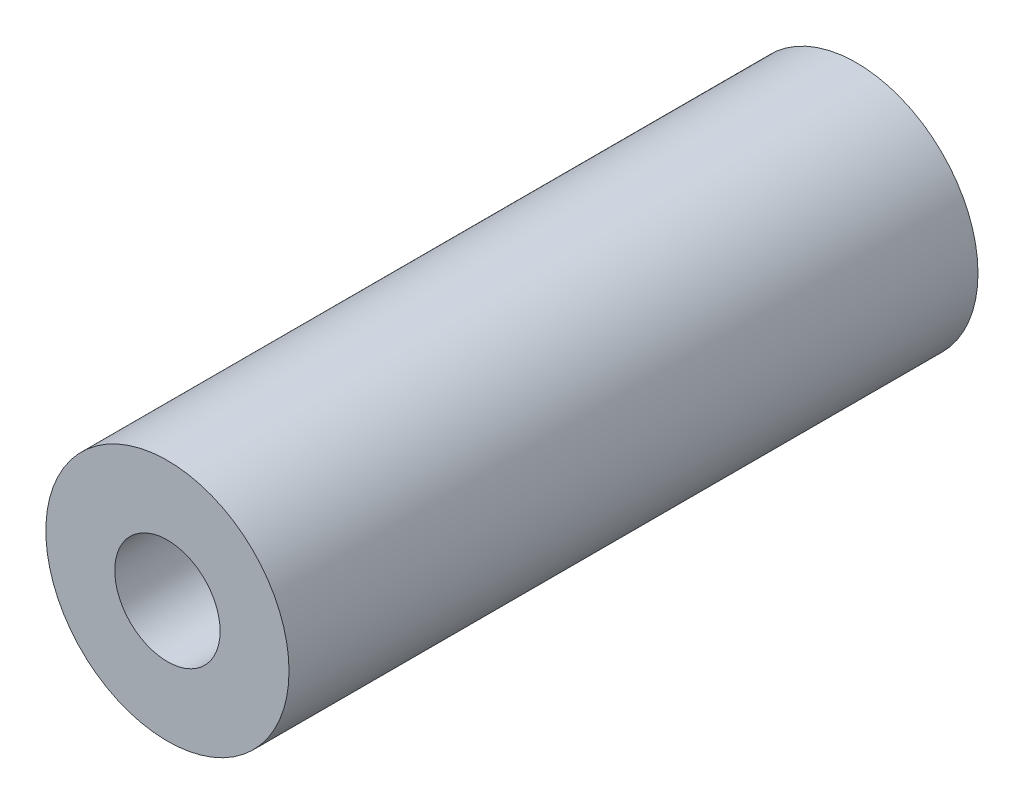
SolidWorks part; units mm, degrees
ref_plane "正面" through (0, 0, 0) normal (0, 0, 1) x (1, 0, 0)
ref_plane "平面" through (0, 0, 0) normal (0, 1, 0) x (1, 0, 0)
ref_plane "右側面" through (0, 0, 0) normal (1, 0, 0) x (0, 0, -1)
sketch "ｽｹｯﾁ1" plane through (0, 0, 0) normal (0, 0, 1) x (1, 0, 0)
  circle A0 centre (0, 0) radius 1.3
  circle A1 centre (0, 0) radius 3
  dimension "D1" = 6
  dimension "D2" = 2.6
extrude "ﾎﾞｽ - 押し出し1" add sketch "ｽｹｯﾁ1" along normal blind 17
